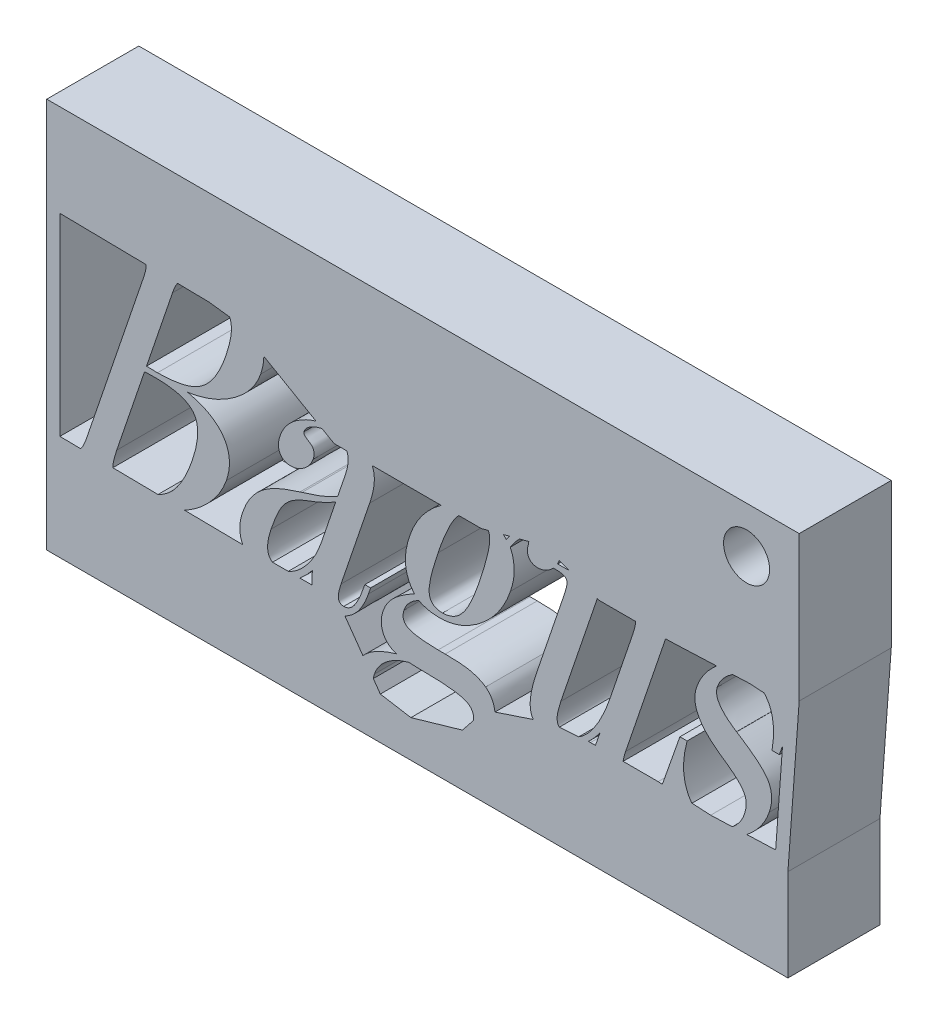
SolidWorks part; units mm, degrees
ref_plane "Front Plane" through (0, 0, 0) normal (0, 0, 1) x (1, 0, 0)
ref_plane "Top Plane" through (0, 0, 0) normal (0, 1, 0) x (1, 0, 0)
ref_plane "Right Plane" through (0, 0, 0) normal (1, 0, 0) x (0, 0, -1)
sketch "Sketch1" plane through (0, 0, 0) normal (0, 0, 1) x (1, 0, 0)
  line L0 (0, 0) -> (54, 0) construction
  text T0 "Bagus" font "Century725 Cn BT" height 16.5
  dimension "D1" = 54
extrude "Boss-Extrude1" add sketch "Sketch1" along normal blind 7
sketch "Sketch2" plane through (0, 0, 0) normal (0, 0, 1) x (1, 0, 0)
  line L3 (12.3987, 16.5) -> (14.68, 16.2138)
  line L4 (14.68, 16.2138) -> (22.1142, 11.9408)
  line L5 (22.1142, 11.9408) -> (32.905, 11.9408)
  line L6 (32.905, 11.9408) -> (37.8611, 13.2434)
  line L7 (37.8611, 13.2434) -> (42.1829, 11.6898)
  line L8 (42.1829, 11.6898) -> (47.3934, 11.6898)
  line L9 (47.3934, 11.6898) -> (53.5198, 11.9408)
  line L10 (53.5198, 11.9408) -> (57.2106, 11.6694)
  line L11 (57.2106, 11.6694) -> (56.3526, 0)
  line L12 (56.3526, 0) -> (50.4702, -0.2171)
  line L13 (50.4702, -0.2171) -> (46.4605, 0)
  line L14 (46.4605, 0) -> (41.3823, 0)
  line L15 (41.3823, 0) -> (38.4853, -0.2171)
  line L16 (38.4853, -0.2171) -> (33.9329, -1.7267)
  line L17 (33.9329, -1.7267) -> (32.1915, -3.9225)
  line L18 (32.1915, -3.9225) -> (27.7488, -5.2105)
  line L19 (27.7488, -5.2105) -> (24.7896, -4.7161)
  line L20 (24.7896, -4.7161) -> (21.5986, -0.2171)
  line L21 (21.5986, -0.2171) -> (16.7239, -0.2171)
  line L22 (16.7239, -0.2171) -> (0, 0)
  line L23 (0, 0) -> (0, 16.6923)
  line L24 (0, 16.6923) -> (12.3987, 16.5)
  line L25 (1, 15.6767) -> (12.3285, 15.501)
  line L26 (12.3285, 15.501) -> (14.356, 15.2466)
  line L27 (14.356, 15.2466) -> (21.8473, 10.9408)
  line L28 (21.8473, 10.9408) -> (33.0342, 10.9408)
  line L29 (33.0342, 10.9408) -> (37.815, 12.1973)
  line L30 (37.815, 12.1973) -> (42.0086, 10.6898)
  line L31 (42.0086, 10.6898) -> (47.4139, 10.6898)
  line L32 (47.4139, 10.6898) -> (53.5036, 10.9393)
  line L33 (53.5036, 10.9393) -> (56.14, 10.7454)
  line L34 (56.14, 10.7454) -> (55.4209, 0.9663)
  line L35 (55.4209, 0.9663) -> (50.4788, 0.7839)
  line L36 (50.4788, 0.7839) -> (46.4876, 1)
  line L37 (46.4876, 1) -> (41.3449, 1)
  line L38 (41.3449, 1) -> (38.2876, 0.7709)
  line L39 (38.2876, 0.7709) -> (33.3348, -0.8714)
  line L40 (33.3348, -0.8714) -> (31.6064, -3.051)
  line L41 (31.6064, -3.051) -> (27.689, -4.1867)
  line L42 (27.689, -4.1867) -> (25.3647, -3.7983)
  line L43 (25.3647, -3.7983) -> (22.1153, 0.7829)
  line L44 (22.1153, 0.7829) -> (16.7304, 0.7829)
  line L45 (16.7304, 0.7829) -> (1, 0.9871)
  line L46 (1, 0.9871) -> (1, 15.6767)
  spline S0 degree 3 poles (12.3987, 16.5) (12.6001, 16.4983) (12.9877, 16.495) (13.5449, 16.4452) (14.0553, 16.3731) (14.5195, 16.2703) (14.9347, 16.1303) (15.305, 15.9656) (15.6279, 15.7685) (15.9014, 15.5392) (16.1314, 15.2842) (16.3004, 14.9938) (16.4265, 14.6801) (16.4958, 14.3379) (16.5153, 13.969) (16.482, 13.5739) (16.4001, 13.1507) (16.3097, 12.8661) (16.2625, 12.7176) knots 0 0 0 0 0.089876 0.172964 0.249493 0.319906 0.384876 0.444743 0.500499 0.553175 0.603606 0.652952 0.702353 0.753933 0.808031 0.866763 0.93052 1 1 1 1 construction
  spline S1 degree 3 poles (33.9329, -1.7267) (33.8859, -1.8534) (33.7923, -2.1059) (33.6017, -2.464) (33.3769, -2.8048) (33.1142, -3.1295) (32.8104, -3.4331) (32.4728, -3.7244) (32.0961, -3.9938) (31.6866, -4.244) (31.2506, -4.4691) (30.7974, -4.6704) (30.3264, -4.837) (29.8407, -4.9708) (29.3409, -5.0826) (28.8234, -5.1535) (28.2914, -5.2049) (27.9309, -5.2086) (27.7488, -5.2105) knots 0 0 0 0 0.05366 0.10693 0.160776 0.215732 0.272615 0.331255 0.392745 0.456486 0.521813 0.587612 0.653423 0.720155 0.787765 0.856787 0.927623 1 1 1 1 construction
  spline S2 degree 3 poles (27.7488, -5.2105) (27.5667, -5.209) (27.2145, -5.2059) (26.7038, -5.1717) (26.2294, -5.1147) (25.79, -5.0365) (25.3837, -4.9411) (25.0137, -4.8141) (24.6768, -4.6698) (24.3766, -4.5045) (24.1184, -4.3194) (23.906, -4.1186) (23.7371, -3.9056) (23.6209, -3.6758) (23.5499, -3.4318) (23.5326, -3.1751) (23.5541, -2.9046) (23.6088, -2.7278) (23.6373, -2.6358) knots 0 0 0 0 0.096201 0.186013 0.270266 0.348548 0.421721 0.490489 0.554972 0.615145 0.671191 0.722322 0.769165 0.814051 0.857544 0.902493 0.949279 1 1 1 1 construction
  dimension "D1" = 1
extrude "Boss-Extrude3" add sketch "Sketch2" along normal blind 7
sketch "Sketch3" plane through (0, 0, 0) normal (0, 0, 1) x (1, 0, 0)
  line L0 (0, 16.6923) -> (0, 22.6923)
  line L1 (57.2106, 11.6694) -> (57.2106, 22.6923)
  line L2 (57.2106, 22.6923) -> (0, 22.6923)
  line L3 (0, 0) -> (0, -7)
  line L4 (56.3526, 0) -> (56.3526, -7)
  line L5 (56.3526, -7) -> (0, -7)
  line L6 (57.2106, 11.6694) -> (53.819, 11.9188) construction
  line L7 (53.5198, 11.9408) -> (53.819, 11.9188) construction
  line L8 (53.5198, 11.9408) -> (53.4045, 11.9361) construction
  line L9 (53.4045, 11.9361) -> (47.3934, 11.6898) construction
  line L10 (47.3934, 11.6898) -> (42.1829, 11.6898) construction
  line L11 (42.1829, 11.6898) -> (38.7828, 12.9121) construction
  line L12 (36.7847, 12.9605) -> (32.905, 11.9408) construction
  line L13 (12.3987, 16.5) -> (0, 16.6923) construction
  line L14 (22.1142, 11.9408) -> (15.9405, 15.4893) construction
  line L15 (32.905, 11.9408) -> (22.1142, 11.9408) construction
  line L16 (57.2106, 11.6694) -> (53.819, 11.9188)
  line L17 (53.5198, 11.9408) -> (53.819, 11.9188)
  line L18 (53.5198, 11.9408) -> (53.4045, 11.9361)
  line L19 (53.4045, 11.9361) -> (47.3934, 11.6898)
  line L20 (47.3934, 11.6898) -> (42.1829, 11.6898)
  line L21 (42.1829, 11.6898) -> (38.7828, 12.9121)
  line L22 (36.7847, 12.9605) -> (32.905, 11.9408)
  line L23 (12.3987, 16.5) -> (0, 16.6923)
  line L24 (22.1142, 11.9408) -> (15.9405, 15.4893)
  line L25 (32.905, 11.9408) -> (22.1142, 11.9408)
  line L26 (50.4702, -0.2171) -> (50.6469, -0.2106) construction
  line L27 (50.6469, -0.2106) -> (56.3526, 0) construction
  line L28 (50.4702, -0.2171) -> (50.0665, -0.1952) construction
  line L29 (46.4605, 0) -> (50.0665, -0.1952) construction
  line L30 (41.3823, 0) -> (46.4605, 0) construction
  line L31 (38.4853, -0.2171) -> (38.9141, -0.185) construction
  line L32 (38.9141, -0.185) -> (41.3823, 0) construction
  line L33 (33.9329, -1.7267) -> (38.4853, -0.2171) construction
  line L34 (21.5986, -0.2171) -> (23.5531, -2.9728) construction
  line L35 (16.7239, -0.2171) -> (21.5986, -0.2171) construction
  line L36 (0, 0) -> (16.7239, -0.2171) construction
  line L37 (50.4702, -0.2171) -> (50.6469, -0.2106)
  line L38 (50.6469, -0.2106) -> (56.3526, 0)
  line L39 (50.4702, -0.2171) -> (50.0665, -0.1952)
  line L40 (46.4605, 0) -> (50.0665, -0.1952)
  line L41 (41.3823, 0) -> (46.4605, 0)
  line L42 (38.4853, -0.2171) -> (38.9141, -0.185)
  line L43 (38.9141, -0.185) -> (41.3823, 0)
  line L44 (33.9329, -1.7267) -> (38.4853, -0.2171)
  line L45 (21.5986, -0.2171) -> (23.5531, -2.9728)
  line L46 (16.7239, -0.2171) -> (21.5986, -0.2171)
  line L47 (0, 0) -> (16.7239, -0.2171)
  spline S0 degree 3 poles (406.5484, 2990.3484) (18.4534, -35.1851) (31.8067, 15.0212) (38.4528, 13.151) (45.4414, 9.2122) (-16.4855, -81.6339) (-317.4523, 2990.9442) knots -8.83486 -8.83486 -8.83486 -8.83486 0.145411 0.272373 0.390617 10.823226 10.823226 10.823226 10.823226 only from (37.8611, 13.2434) to (38.7828, 12.9121) construction
  spline S1 degree 3 poles (2985.5577, 528.0002) (76.7031, -189.2161) (18.0184, 7.5651) (44.6495, 15.3043) (59.9532, -35.1063) (-385.8882, 2982.8795) knots -15.251034 -15.251034 -15.251034 -15.251034 0.796856 0.900964 6.979356 6.979356 6.979356 6.979356 only from (36.7847, 12.9605) to (37.8611, 13.2434) construction
  spline S2 degree 3 poles (96.2595, 3015.0661) (-17.715, -25.5929) (-1.2271, 17.7664) (13.5449, 16.4452) (14.0553, 16.3731) (14.5195, 16.2703) (14.9347, 16.1303) (15.305, 15.9656) (15.6279, 15.7685) (23.2829, 9.3523) (-9.0527, -39.9679) (-2821.0788, -958.6914) knots -6.365365 -6.365365 -6.365365 -6.365365 0.089876 0.172964 0.249493 0.319906 0.384876 0.444743 0.500499 0.553175 4.89089 4.89089 4.89089 4.89089 only from (12.3987, 16.5) to (15.9405, 15.4893) construction
  spline S3 degree 3 poles (37.8611, 13.2434) (37.9691, 13.2388) (38.1714, 13.2301) (38.4528, 13.151) (38.6538, 13.0377) (38.7516, 12.9459) (38.7828, 12.9121) knots 0 0 0 0 0.145411 0.272373 0.390617 0.452476 0.452476 0.452476 0.452476
  spline S4 degree 3 poles (36.7847, 12.9605) (36.8937, 13.0166) (37.1246, 13.1175) (37.4864, 13.2226) (37.7383, 13.2366) (37.8611, 13.2434) knots 0.697926 0.697926 0.697926 0.697926 0.796856 0.900964 1 1 1 1
  spline S5 degree 3 poles (12.3987, 16.5) (12.6001, 16.4983) (12.9877, 16.495) (13.5449, 16.4452) (14.0553, 16.3731) (14.5195, 16.2703) (14.9347, 16.1303) (15.305, 15.9656) (15.6279, 15.7685) (15.8293, 15.5997) (15.927, 15.503) (15.9405, 15.4893) knots 0 0 0 0 0.089876 0.172964 0.249493 0.319906 0.384876 0.444743 0.500499 0.553175 0.561723 0.561723 0.561723 0.561723
  spline S6 degree 3 poles (2798.0597, -1167.3204) (0.4958, 32.9074) (38.1868, 6.1488) (33.6017, -2.464) (33.3769, -2.8048) (33.1142, -3.1295) (32.8104, -3.4331) (32.4728, -3.7244) (32.0961, -3.9938) (31.6866, -4.244) (31.2506, -4.4691) (30.7974, -4.6704) (30.3264, -4.837) (29.8407, -4.9708) (29.3409, -5.0826) (28.8234, -5.1535) (15.1646, -6.4741) (-0.4815, 35.9414) (136.3124, -3003.0103) knots -3.706332 -3.706332 -3.706332 -3.706332 0.05366 0.10693 0.160776 0.215732 0.272615 0.331255 0.392745 0.456486 0.521813 0.587612 0.653423 0.720155 0.787765 0.856787 0.927623 6.237221 6.237221 6.237221 6.237221 only from (33.9329, -1.7267) to (27.7488, -5.2105) construction
  spline S7 degree 3 poles (-18.9804, -3004.5685) (58.4581, 31.2217) (42.0748, -6.2014) (26.7038, -5.1717) (26.2294, -5.1147) (25.79, -5.0365) (25.3837, -4.9411) (25.0137, -4.8141) (24.6768, -4.6698) (24.3766, -4.5045) (24.1184, -4.3194) (23.906, -4.1186) (23.7371, -3.9056) (23.6209, -3.6758) (23.5499, -3.4318) (22.9639, 5.2685) (85.0074, 14.1171) (2490.7603, -1708.6683) knots -7.864143 -7.864143 -7.864143 -7.864143 0.096201 0.186013 0.270266 0.348548 0.421721 0.490489 0.554972 0.615145 0.671191 0.722322 0.769165 0.814051 0.857544 0.902493 5.39785 5.39785 5.39785 5.39785 only from (27.7488, -5.2105) to (23.5531, -2.9728) construction
  spline S8 degree 3 poles (33.9329, -1.7267) (33.8859, -1.8534) (33.7923, -2.1059) (33.6017, -2.464) (33.3769, -2.8048) (33.1142, -3.1295) (32.8104, -3.4331) (32.4728, -3.7244) (32.0961, -3.9938) (31.6866, -4.244) (31.2506, -4.4691) (30.7974, -4.6704) (30.3264, -4.837) (29.8407, -4.9708) (29.3409, -5.0826) (28.8234, -5.1535) (28.2914, -5.2049) (27.9309, -5.2086) (27.7488, -5.2105) knots 0 0 0 0 0.05366 0.10693 0.160776 0.215732 0.272615 0.331255 0.392745 0.456486 0.521813 0.587612 0.653423 0.720155 0.787765 0.856787 0.927623 1 1 1 1
  spline S9 degree 3 poles (27.7488, -5.2105) (27.5667, -5.209) (27.2145, -5.2059) (26.7038, -5.1717) (26.2294, -5.1147) (25.79, -5.0365) (25.3837, -4.9411) (25.0137, -4.8141) (24.6768, -4.6698) (24.3766, -4.5045) (24.1184, -4.3194) (23.906, -4.1186) (23.7371, -3.9056) (23.6209, -3.6758) (23.5499, -3.4318) (23.5339, -3.195) (23.5436, -3.0408) (23.5531, -2.9728) knots 0 0 0 0 0.096201 0.186013 0.270266 0.348548 0.421721 0.490489 0.554972 0.615145 0.671191 0.722322 0.769165 0.814051 0.857544 0.902493 0.938777 0.938777 0.938777 0.938777
  dimension "D1" = 6
  dimension "D2" = 7
extrude "Boss-Extrude4" add sketch "Sketch3" along normal blind 7
sketch "Sketch4" plane through (0, 0, 7) normal (0, 0, 1) x (1, 0, 0)
  line L0 (57.2106, 11.6694) -> (57.2106, 22.6923) construction
  line L1 (57.2106, 22.6923) -> (0, 22.6923) construction
  circle A0 centre (53.2106, 19.1923) radius 1.75
  dimension "D3" = 3.5
  dimension "D1" = 4
  dimension "D2" = 3.5
extrude "Cut-Extrude1" cut sketch "Sketch4" against normal through all
